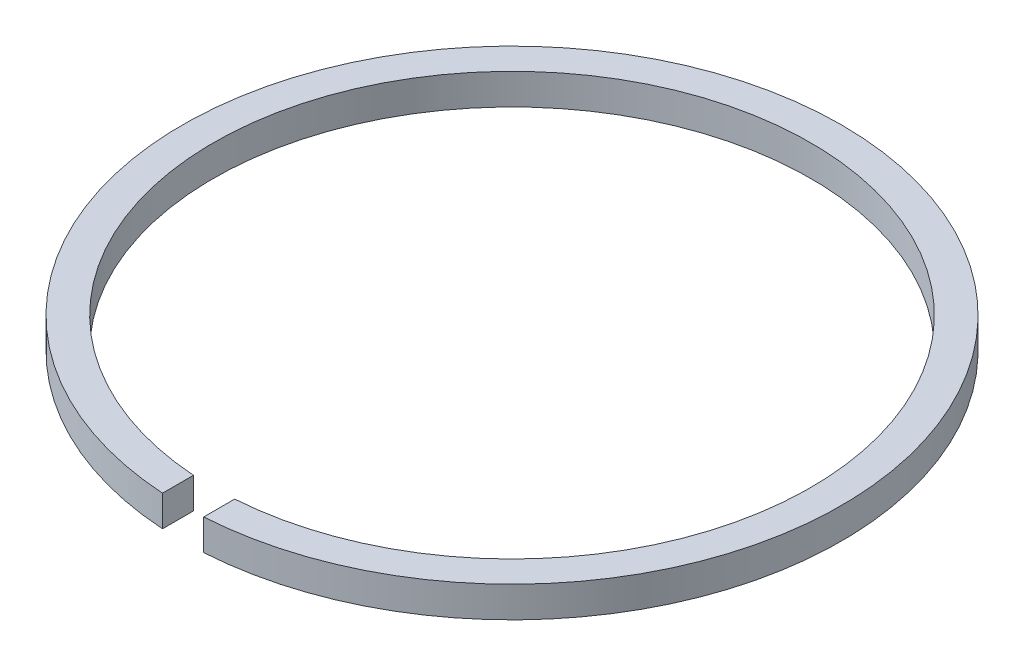
SolidWorks part; units mm, degrees
ref_plane "Front Plane" through (0, 0, 0) normal (0, 0, 1) x (1, 0, 0)
ref_plane "Top Plane" through (0, 0, 0) normal (0, 1, 0) x (1, 0, 0)
ref_plane "Right Plane" through (0, 0, 0) normal (1, 0, 0) x (0, 0, -1)
sketch "Sketch1" plane through (0, 0, 0) normal (0, 1, 0) x (1, 0, 0)
  line L1 (1, -14.4655) -> (1, -15.9687)
  line L2 (-1, -14.4655) -> (-1, -15.9687)
  arc A0 (1, -15.9687) -> (-1, -15.9687) centre (0, 0) ccw
  arc A1 (1, -14.4655) -> (-1, -14.4655) centre (0, 0) ccw
  dimension "D1" = 32
  dimension "D2" = 29
  dimension "D3" = 2
extrude "Boss-Extrude2" add sketch "Sketch1" along normal blind 1.5
